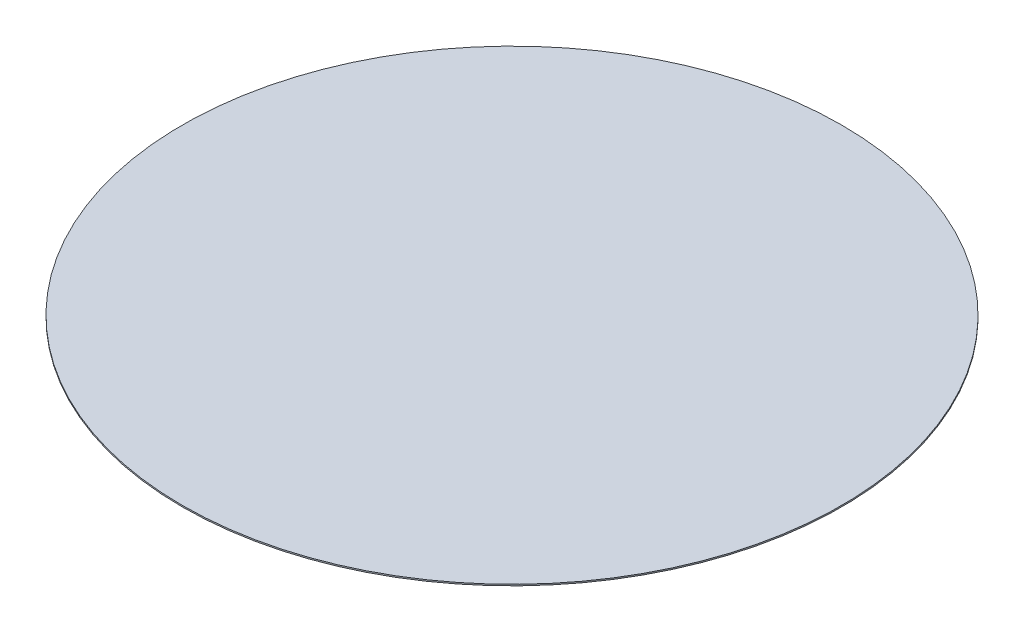
SolidWorks part; units mm, degrees
ref_plane "Front Plane" through (0, 0, 0) normal (0, 0, 1) x (1, 0, 0)
ref_plane "Top Plane" through (0, 0, 0) normal (0, 1, 0) x (1, 0, 0)
ref_plane "Right Plane" through (0, 0, 0) normal (1, 0, 0) x (0, 0, -1)
sketch "Sketch1" plane through (0, 0, 0) normal (0, 1, 0) x (1, 0, 0)
  circle A0 centre (0, 0) radius 24
  dimension "D1" = 48
extrude "Boss-Extrude1" add sketch "Sketch1" along normal blind 0.1
sketch "Sketch3" plane through (0, 0.1, 0) normal (0, 1, 0) x (1, 0, 0)
  line L0 (-1171.8674, 559.7869) -> (-211.8674, 559.7869) construction
